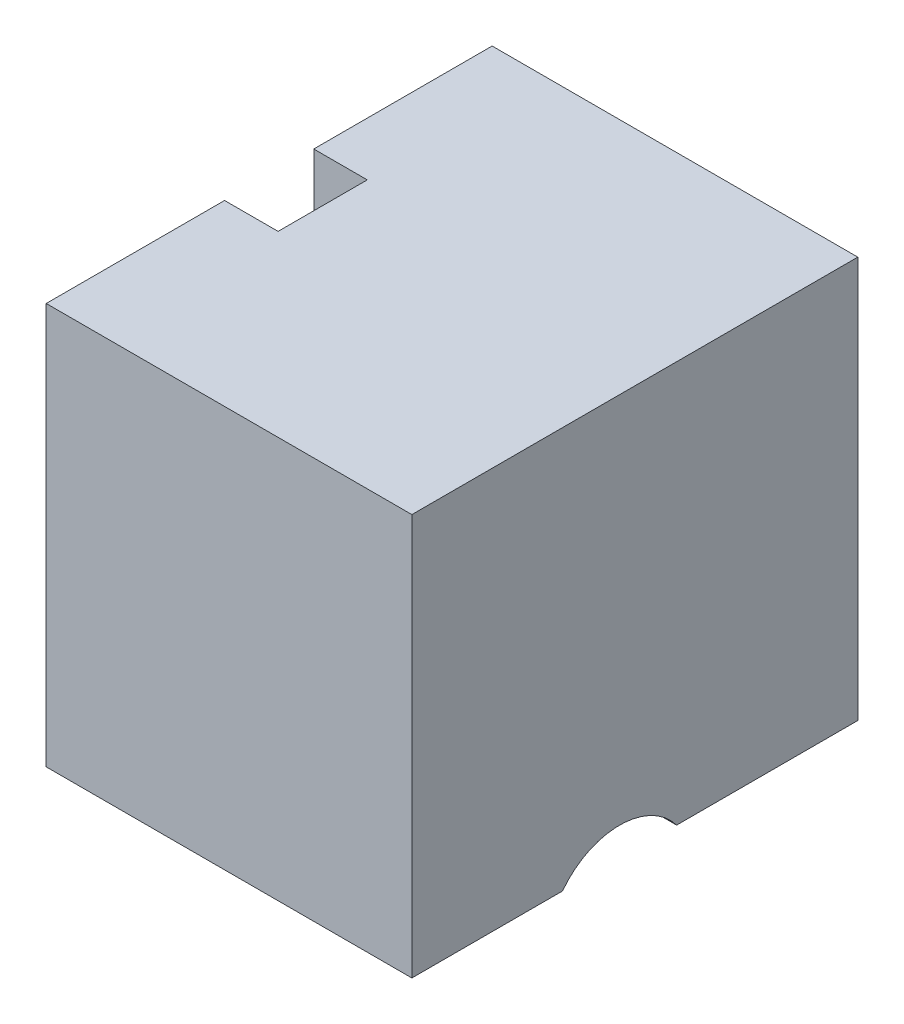
SolidWorks part; units mm, degrees
ref_plane "Front Plane" through (0, 0, 0) normal (0, 0, 1) x (1, 0, 0)
ref_plane "Top Plane" through (0, 0, 0) normal (0, 1, 0) x (1, 0, 0)
ref_plane "Right Plane" through (0, 0, 0) normal (1, 0, 0) x (0, 0, -1)
sketch "Sketch1" plane through (0, 0, 0) normal (0, 1, 0) x (1, 0, 0)
  line L0 (26.9335, 26.7086) -> (26.9335, -23.2914)
  line L1 (26.9335, -23.2914) -> (-14.0665, -23.2914)
  line L3 (26.9335, 26.7086) -> (-14.0665, 26.7086)
  line L4 (-14.0665, -23.2914) -> (-14.0665, 26.7086)
  point P0 (0, 0)
  point P5 (22.4699, -23.0918)
  point P8 (0, 0)
  dimension "D1" = 50
  dimension "D2" = 41
extrude "Boss-Extrude1" add sketch "Sketch1" along normal blind 45
sketch "Sketch2" plane through (0, 45, 0) normal (0, 1, 0) x (1, 0, 0)
  line L0 (-14.0665, 26.7086) -> (-14.0665, -23.2914) construction
  line L1 (-20.0665, 6.7086) -> (-8.0665, 6.7086)
  line L2 (-20.0665, 6.7086) -> (-20.0665, -3.2914)
  line L3 (-20.0665, -3.2914) -> (-8.0665, -3.2914)
  line L4 (-8.0665, 6.7086) -> (-8.0665, -3.2914)
  line L5 (-20.0665, 6.7086) -> (-8.0665, -3.2914) construction
  line L6 (-20.0665, -3.2914) -> (-8.0665, 6.7086) construction
  point P0 (-14.0665, 1.7086)
extrude "Cut-Extrude1" cut sketch "Sketch2" against normal blind 10 and the other way through all
sketch "Sketch3" plane through (26.9335, 0, 0) normal (1, 0, 0) x (0, 0, -1)
  circle A0 centre (0, -4.8046) radius 8
extrude "Cut-Extrude2" cut sketch "Sketch3" against normal through all both
